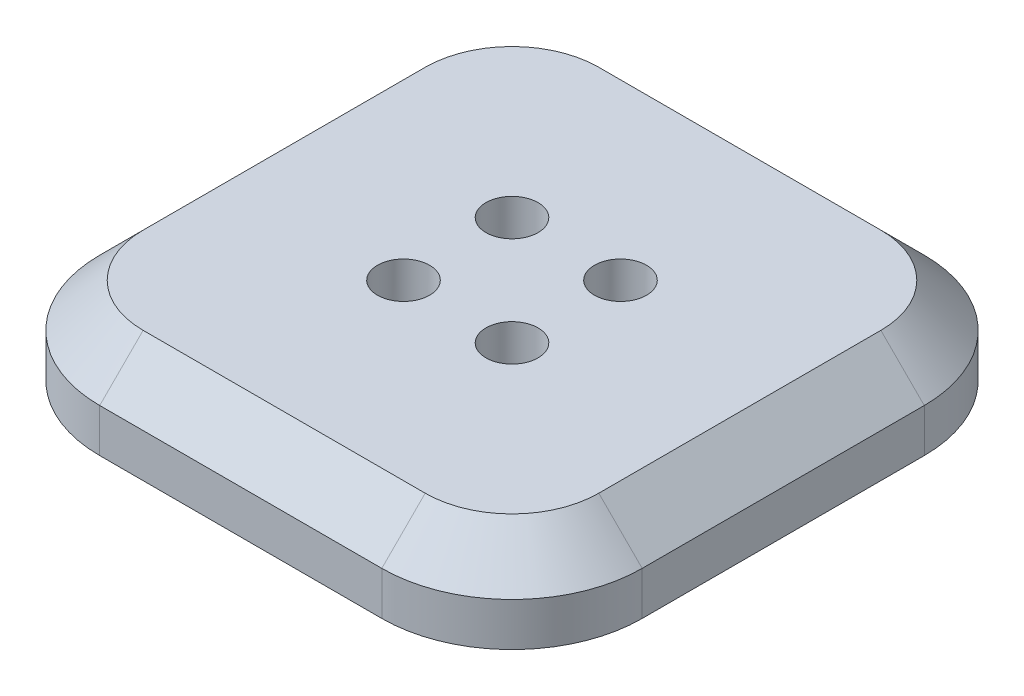
SolidWorks part; units mm, degrees
ref_plane "Front Plane" through (0, 0, 0) normal (0, 0, 1) x (1, 0, 0)
ref_plane "Top Plane" through (0, 0, 0) normal (0, 1, 0) x (1, 0, 0)
ref_plane "Right Plane" through (0, 0, 0) normal (1, 0, 0) x (0, 0, -1)
sketch "Sketch1" plane through (0, 0, 0) normal (0, 1, 0) x (1, 0, 0)
  line L0 (-32.5, 62.5) -> (32.5, 62.5)
  line L1 (62.5, 32.5) -> (62.5, -32.5)
  line L2 (32.5, -62.5) -> (-32.5, -62.5)
  line L3 (-62.5, -32.5) -> (-62.5, 32.5)
  arc A0 (-32.5, -62.5) -> (-62.5, -32.5) centre (-32.5, -32.5) cw
  arc A1 (62.5, -32.5) -> (32.5, -62.5) centre (32.5, -32.5) cw
  arc A2 (32.5, 62.5) -> (62.5, 32.5) centre (32.5, 32.5) cw
  arc A3 (-32.5, 62.5) -> (-62.5, 32.5) centre (-32.5, 32.5) ccw
  point P4 (0, 62.5)
  point P5 (-62.5, 0)
  point P13 (62.5, 62.5)
  point P16 (-62.5, 62.5)
  dimension "D2" = 30
  dimension "D1" = 125
extrude "Boss-Extrude1" add sketch "Sketch1" along normal mid plane 20
chamfer "Chamfer1" distance 10 angle 45 8 edges at (-62.5, 10, 0) (-53.7132, 10, -53.7132) (0, 10, -62.5) (53.7132, 10, -53.7132) (62.5, 10, 0) (53.7132, 10, 53.7132) (0, 10, 62.5) (-53.7132, 10, 53.7132)
sketch "Sketch2" plane through (0, 10, 0) normal (0, 1, 0) x (1, 0, 0)
  line L0 (12.5, 62.5) -> (12.5, -62.5) construction
  line L3 (-32.5, 62.5) -> (32.5, 62.5) construction
  line L4 (32.5, -62.5) -> (-32.5, -62.5) construction
  line L5 (-62.5, -32.5) -> (-62.5, 32.5) construction
  line L6 (-62.5, 12.5) -> (62.5, 12.5) construction
  line L7 (62.5, 32.5) -> (62.5, -32.5) construction
  line L8 (-148.0334, 0) -> (62.5, 0) construction
  line L9 (0, 62.5) -> (0, -62.5) construction
  circle A0 centre (12.5, 12.5) radius 6
  circle A1 centre (-12.5, 12.5) radius 6
  circle A2 centre (12.5, -12.5) radius 6
  circle A3 centre (-12.5, -12.5) radius 6
  dimension "D1" = 50
  dimension "D2" = 50
extrude "Cut-Extrude1" cut sketch "Sketch2" against normal offset from surface (10 mm away) 10 up to face at (0, 10, 0)
sketch "Sketch3" plane through (0, -10, 0) normal (0, -1, 0) x (1, 0, 0)
  line L0 (37.5, 62.5) -> (37.5, -62.5) construction
  line L1 (-32.5, 62.5) -> (32.5, 62.5) construction
  line L2 (32.5, -62.5) -> (-32.5, -62.5) construction
  line L3 (-62.5, 37.5) -> (62.5, 37.5) construction
  line L4 (-62.5, -32.5) -> (-62.5, 32.5) construction
  line L5 (62.5, 32.5) -> (62.5, -32.5) construction
  line L6 (0, 62.5) -> (0, -62.5) construction
  line L7 (-62.5, 0) -> (62.5, 0) construction
  circle A0 centre (37.5, 37.5) radius 6
  circle A1 centre (-37.5, 37.5) radius 6
  circle A2 centre (37.5, -37.5) radius 6
  circle A3 centre (-37.5, -37.5) radius 6
  dimension "D1" = 25
  dimension "D2" = 25
extrude "Cut-Extrude2" cut sketch "Sketch3" against normal offset from surface (10 mm away) 10 up to face at (0, -10, 0)
